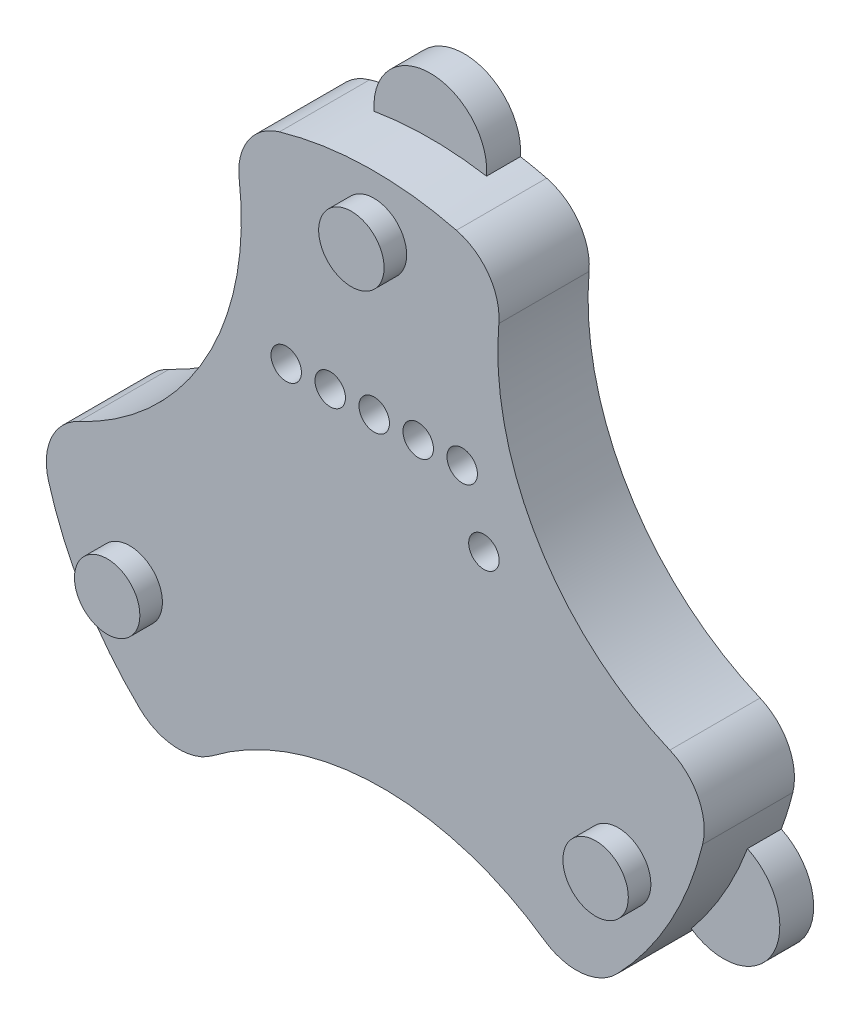
SolidWorks part; units mm, degrees
ref_plane "Спереди" through (0, 0, 0) normal (0, 0, 1) x (1, 0, 0)
ref_plane "Сверху" through (0, 0, 0) normal (0, 1, 0) x (1, 0, 0)
ref_plane "Справа" through (0, 0, 0) normal (1, 0, 0) x (0, 0, -1)
sketch "Sketch1" plane through (0, 0, 0) normal (0, 0, 1) x (1, 0, 0)
  line L0 (3.9, 6.755) -> (7.8, 0) construction
  line L2 (5.85, 10.1325) -> (11.7, 0) construction
  line L4 (7.8, 13.51) -> (15.6, 0) construction
  circle A61 centre (0, 0) radius 20
  circle A131 centre (0, 0) radius 1.25
  circle A484 centre (3.9, 0) radius 1.25
  circle A485 centre (7.8, 0) radius 1.25
  circle A486 centre (11.7, 0) radius 1.25
  circle A487 centre (15.6, 0) radius 1.25
  circle A488 centre (1.95, -3.3775) radius 1.25
  circle A489 centre (3.9, -6.755) radius 1.25
  circle A490 centre (5.85, -10.1325) radius 1.25
  circle A491 centre (7.8, -13.51) radius 1.25
  circle A492 centre (-1.95, -3.3775) radius 1.25
  circle A493 centre (-3.9, -6.755) radius 1.25
  circle A494 centre (-5.85, -10.1325) radius 1.25
  circle A495 centre (-7.8, -13.51) radius 1.25
  circle A496 centre (-3.9, 0) radius 1.25
  circle A497 centre (-7.8, 0) radius 1.25
  circle A498 centre (-11.7, 0) radius 1.25
  circle A499 centre (-15.6, 0) radius 1.25
  circle A500 centre (-1.95, 3.3775) radius 1.25
  circle A501 centre (-3.9, 6.755) radius 1.25
  circle A502 centre (-5.85, 10.1325) radius 1.25
  circle A503 centre (-7.8, 13.51) radius 1.25
  circle A504 centre (1.95, 3.3775) radius 1.25
  circle A505 centre (3.9, 6.755) radius 1.25
  circle A506 centre (5.85, 10.1325) radius 1.25
  circle A507 centre (7.8, 13.51) radius 1.25
  circle A508 centre (5.85, 3.3775) radius 1.25
  circle A509 centre (7.8, 6.755) radius 1.25
  circle A510 centre (9.75, 3.3775) radius 1.25
  circle A511 centre (11.7, 6.755) radius 1.25
  circle A512 centre (9.7491, 10.1341) radius 1.25
  circle A513 centre (13.6509, 3.3759) radius 1.25
  circle A514 centre (5.85, -3.3791) radius 1.25
  circle A515 centre (9.75, -3.3791) radius 1.25
  circle A516 centre (7.8, -6.7566) radius 1.25
  circle A517 centre (11.7, -6.7566) radius 1.25
  circle A518 centre (9.7491, -10.1356) radius 1.25
  circle A519 centre (13.6509, -3.3775) radius 1.25
  circle A520 centre (-0.0013, -6.7573) radius 1.25
  circle A521 centre (1.9487, -10.1348) radius 1.25
  circle A522 centre (-1.9513, -10.1348) radius 1.25
  circle A523 centre (-0.0013, -13.5123) radius 1.25
  circle A524 centre (-3.9032, -13.5123) radius 1.25
  circle A525 centre (3.9005, -13.5123) radius 1.25
  circle A526 centre (-5.8527, -3.3791) radius 1.25
  circle A527 centre (-7.8027, -6.7566) radius 1.25
  circle A528 centre (-9.7527, -3.3791) radius 1.25
  circle A529 centre (-11.7027, -6.7566) radius 1.25
  circle A530 centre (-13.6536, -3.3775) radius 1.25
  circle A531 centre (-9.7518, -10.1356) radius 1.25
  circle A532 centre (-5.8527, 3.3775) radius 1.25
  circle A533 centre (-9.7527, 3.3775) radius 1.25
  circle A534 centre (-7.8027, 6.755) radius 1.25
  circle A535 centre (-11.7027, 6.755) radius 1.25
  circle A536 centre (-9.7518, 10.1341) radius 1.25
  circle A537 centre (-13.6536, 3.3759) radius 1.25
  circle A538 centre (-0.0014, 6.7558) radius 1.25
  circle A539 centre (-1.9514, 10.1333) radius 1.25
  circle A540 centre (1.9486, 10.1333) radius 1.25
  circle A541 centre (-0.0014, 13.5108) radius 1.25
  circle A542 centre (3.9005, 13.5108) radius 1.25
  circle A543 centre (-3.9032, 13.5108) radius 1.25
  circle A544 centre (13.65, -1.1258) radius 2.2517 construction
  circle A545 centre (11.7009, -4.5044) radius 2.2522 construction
  circle A546 centre (9.75, -7.8834) radius 2.2522 construction
  circle A547 centre (7.7987, -11.2591) radius 2.2509 construction
  circle A548 centre (13.65, -1.1258) radius 0.65
  circle A549 centre (11.7009, -4.5044) radius 0.65
  circle A550 centre (9.75, -7.8834) radius 0.65
  circle A551 centre (7.7987, -11.2591) radius 0.65
  circle A552 centre (9.75, -1.1258) radius 0.65
  circle A553 centre (7.8009, -4.5044) radius 0.65
  circle A554 centre (5.85, -7.8834) radius 0.65
  circle A555 centre (3.8987, -11.2591) radius 0.65
  circle A556 centre (5.85, -1.1258) radius 0.65
  circle A557 centre (3.9009, -4.5044) radius 0.65
  circle A558 centre (1.95, -7.8834) radius 0.65
  circle A559 centre (-0.0013, -11.2591) radius 0.65
  circle A560 centre (1.95, -1.1258) radius 0.65
  circle A561 centre (0.0009, -4.5044) radius 0.65
  circle A562 centre (-1.95, -7.8834) radius 0.65
  circle A563 centre (-3.9013, -11.2591) radius 0.65
  circle A564 centre (-1.95, -1.1258) radius 0.65
  circle A565 centre (-3.8991, -4.5044) radius 0.65
  circle A566 centre (-5.85, -7.8834) radius 0.65
  circle A567 centre (-7.8013, -11.2591) radius 0.65
  circle A568 centre (-5.85, -1.1258) radius 0.65
  circle A569 centre (-7.7991, -4.5044) radius 0.65
  circle A570 centre (-9.75, -7.8834) radius 0.65
  circle A572 centre (-9.75, -1.1258) radius 0.65
  circle A573 centre (-11.6991, -4.5044) radius 0.65
  circle A576 centre (-13.65, -1.1258) radius 0.65
  circle A587 centre (0, 2.2517) radius 2.2517 construction
  circle A588 centre (0, 2.2517) radius 0.65
  circle A589 centre (3.9, 2.2517) radius 0.65
  circle A590 centre (7.8, 2.2517) radius 0.65
  circle A591 centre (11.7, 2.2517) radius 0.65
  circle A592 centre (15.6, 2.2517) radius 0.65
  circle A593 centre (1.9491, 5.6297) radius 2.2522 construction
  circle A594 centre (1.9491, 5.6297) radius 0.65
  circle A595 centre (5.8491, 5.6297) radius 0.65
  circle A596 centre (9.7491, 5.6297) radius 0.65
  circle A597 centre (13.6491, 5.6297) radius 0.65
  circle A598 centre (3.8991, 9.0072) radius 2.2522 construction
  circle A599 centre (3.8991, 9.0072) radius 0.65
  circle A600 centre (7.7991, 9.0072) radius 0.65
  circle A601 centre (11.6991, 9.0072) radius 0.65
  circle A602 centre (5.85, 12.3842) radius 2.2517 construction
  circle A603 centre (5.85, 12.3842) radius 0.65
  circle A604 centre (9.75, 12.3842) radius 0.65
  circle A605 centre (5.85, -14.6358) radius 0.65
  circle A606 centre (1.9509, -14.6353) radius 0.65
  circle A607 centre (-1.9491, -14.6353) radius 0.65
  circle A608 centre (-5.85, -14.6358) radius 0.65
  circle A609 centre (-15.6, 2.2517) radius 0.65
  circle A610 centre (-13.65, 5.6281) radius 0.65
  circle A611 centre (-11.7, 9.0056) radius 0.65
  circle A612 centre (-9.75, 12.3842) radius 0.65
  circle A613 centre (-5.85, 12.3842) radius 0.65
  circle A614 centre (-1.95, 12.3842) radius 0.65
  circle A615 centre (1.95, 12.3842) radius 0.65
  circle A616 centre (-7.8, 9.0056) radius 0.65
  circle A617 centre (-9.75, 5.6281) radius 0.65
  circle A618 centre (-11.7, 2.2517) radius 0.65
  circle A619 centre (-3.9, 9.0056) radius 0.65
  circle A620 centre (-5.85, 5.6281) radius 0.65
  circle A621 centre (-7.8, 2.2517) radius 0.65
  circle A622 centre (0, 9.0056) radius 0.65
  circle A623 centre (-1.95, 5.6281) radius 0.65
  circle A624 centre (-3.9, 2.2517) radius 0.65
  circle A625 centre (-15.5991, -4.5044) radius 0.65
  circle A626 centre (-13.65, -7.8834) radius 0.65
  circle A627 centre (-17.55, -7.8834) radius 0.65
  circle A628 centre (-19.5013, -11.2591) radius 0.65
  circle A629 centre (-15.6013, -11.2591) radius 0.65
  circle A630 centre (-11.7013, -11.2591) radius 0.65
  point P51 (0, 0)
  point P125 (-0.0013, -0.0008)
  point P231 (0, 0)
  dimension "D1" = 5
  dimension "D3" = 6
  dimension "D5" = 8
  dimension "D7" = 4
  dimension "D11" = 4
  dimension "D2" = 6
  dimension "D6" = 5
  dimension "D8" = 3
  dimension "D9" = 2
  dimension "D4" = 1.3
  dimension "D10" = 3
ref_plane "Plane1" through (0, 0, 10) normal (0, 0, 1) x (1, 0, 0)
sketch "Sketch2" plane through (0, 0, 10) normal (0, 0, 1) x (1, 0, 0)
  circle A52 centre (0, 0) radius 16.85 construction
  circle A53 centre (0, 0) radius 18.85
  circle A80 centre (7.8243, 11.3015) radius 1.3501
  circle A81 centre (5.85, 12.3842) radius 2.2517 construction
  circle A82 centre (3.9243, 11.3015) radius 1.3501
  circle A83 centre (0.0243, 11.3015) radius 1.3501
  circle A84 centre (-3.8757, 11.3015) radius 1.3501
  circle A85 centre (-7.7757, 11.3015) radius 1.3501
  circle A86 centre (9.7491, 5.6297) radius 1.3501
  circle A87 centre (0, 0) radius 11.2578 construction
  dimension "D15" = 2
  dimension "D2" = 5
extrude "Boss-Extrude1" add sketch "Sketch2" along normal blind 8
sketch "Sketch3" plane through (0, 0, 18) normal (0, 0, 1) x (1, 0, 0)
  circle A0 centre (0, 0) radius 17.6
  circle A1 centre (0, 0) radius 30
extrude "Boss-Extrude2" add sketch "Sketch3" against normal up to surface (8 mm away) up to face at (18.85, 0, 10)
sketch "Sketch4" plane through (0, 0, 18) normal (0, 0, 1) x (1, 0, 0)
  circle A0 centre (0, 0) radius 25 construction
  circle A1 centre (0, 25) radius 2.9
  circle A2 centre (21.6506, -12.5) radius 2.9
  circle A3 centre (-21.6506, -12.5) radius 2.9
  point P11 (0, 0)
  dimension "D1" = 3
extrude "Boss-Extrude3" add sketch "Sketch4" along normal blind 2
sketch "Sketch6" plane through (0, 0, 10) normal (0, 0, -1) x (-1, 0, 0)
  circle A0 centre (0, 30) radius 5
  circle A1 centre (0, 0) radius 30 construction
  circle A2 centre (25.9808, -15) radius 5
  circle A3 centre (-25.9808, -15) radius 5
  point P10 (0, 0)
  dimension "D1" = 3
extrude "Boss-Extrude4" add sketch "Sketch6" against normal blind 3
sketch "Sketch5" plane through (0, 0, 10) normal (0, 0, -1) x (-1, 0, 0)
  circle A0 centre (0, 25) radius 3
  circle A1 centre (21.6506, -12.5) radius 3
  circle A2 centre (-21.6506, -12.5) radius 3
extrude "Cut-Extrude1" cut sketch "Sketch5" against normal blind 3
sketch "Sketch7" plane through (0, 0, 10) normal (0, 0, -1) x (-1, 0, 0)
  line L0 (0, 0) -> (-35.9801, 21.6664) construction
  circle A0 centre (0, 0) radius 42 construction
  circle A1 centre (-35.9801, 21.6664) radius 25
  circle A2 centre (36.7537, 20.3265) radius 25
  circle A3 centre (-0.7736, -41.9929) radius 25
  point P11 (0, 0)
  dimension "D1" = 3
extrude "Cut-Extrude2" cut sketch "Sketch7" against normal blind 8
fillet "Fillet1" radius 5 6 edges at (-29.7735, -3.6793, 14) (-12.7099, 27.1746, 14) (18.0731, -23.945, 14) (-17.1789, -24.5944, 14) (11.7004, 27.6243, 14) (29.8888, -2.5802, 14)
sketch "Sketch8"
sketch_block_instance "Block1-1"
sketch_block "Block1" parameters "D1"=2, "D2"=3
sketch_block_instance "Block3-1"
sketch_block "Block3" parameters "D1"=2, "D2"=3
sketch "Sketch9" plane through (0, 0, 0) normal (0, 0, 1) x (1, 0, 0)
  line L0 (-7.8, 13.51) -> (-7.8027, 6.755) construction
  line L1 (-9.7518, 10.1341) -> (-5.85, 10.1325) construction
  line L2 (-7.8008, 11.6325) -> (-7.8019, 8.6325) construction
  line L3 (-6.8008, 11.6321) -> (-6.8019, 8.6321)
  line L4 (-8.8008, 11.6329) -> (-8.8019, 8.6329)
  line L5 (-4.9008, 11.6329) -> (-4.9019, 8.6329)
  line L6 (-2.9008, 11.6321) -> (-2.9019, 8.6321)
  line L7 (-3.9008, 11.6325) -> (-3.9019, 8.6325) construction
  line L8 (-1.0008, 11.6329) -> (-1.0019, 8.6329)
  line L9 (0.9992, 11.6321) -> (0.9981, 8.6321)
  line L10 (-0.0008, 11.6325) -> (-0.0019, 8.6325) construction
  line L11 (2.8992, 11.6329) -> (2.8981, 8.6329)
  line L12 (4.8992, 11.6321) -> (4.8981, 8.6321)
  line L13 (3.8992, 11.6325) -> (3.8981, 8.6325) construction
  line L14 (6.7992, 11.6329) -> (6.7981, 8.6329)
  line L15 (8.7992, 11.6321) -> (8.7981, 8.6321)
  line L16 (7.7992, 11.6325) -> (7.7981, 8.6325) construction
  line L17 (-9.7518, 10.1341) -> (-9.7527, 3.3775) construction
  line L18 (-11.7027, 6.755) -> (-7.8027, 6.755) construction
  line L19 (-10.7035, 1.877) -> (-10.702, 4.877)
  line L22 (-9.7527, 3.3775) -> (-5.8527, 3.3775) construction
  line L25 (-7.8027, 6.755) -> (-7.8, 0) construction
  line L26 (-7.8035, 1.8775) -> (-7.8019, 4.8775) construction
  line L27 (-8.8035, 1.878) -> (-8.8019, 4.878)
  line L28 (-6.8035, 1.877) -> (-6.8019, 4.877)
  line L29 (-2.9035, 1.877) -> (-2.9019, 4.877)
  line L30 (-4.9035, 1.878) -> (-4.9019, 4.878)
  line L31 (-3.9035, 1.8775) -> (-3.9019, 4.8775) construction
  line L32 (0.9965, 1.877) -> (0.9981, 4.877)
  line L33 (-1.0035, 1.878) -> (-1.0019, 4.878)
  line L34 (-0.0035, 1.8775) -> (-0.0019, 4.8775) construction
  line L35 (4.8965, 1.877) -> (4.8981, 4.877)
  line L36 (2.8965, 1.878) -> (2.8981, 4.878)
  line L37 (3.8965, 1.8775) -> (3.8981, 4.8775) construction
  line L38 (8.7965, 1.877) -> (8.7981, 4.877)
  line L39 (6.7965, 1.878) -> (6.7981, 4.878)
  line L40 (7.7965, 1.8775) -> (7.7981, 4.8775) construction
  line L41 (12.6965, 1.877) -> (12.6981, 4.877)
  line L42 (10.6965, 1.878) -> (10.6981, 4.878)
  line L43 (11.6965, 1.8775) -> (11.6981, 4.8775) construction
  line L44 (-12.7035, 1.878) -> (-12.7019, 4.878)
  line L45 (-11.7035, 1.8775) -> (-11.702, 4.8775) construction
  line L46 (-9.7527, -3.3791) -> (-5.8527, -3.3791) construction
  line L47 (-7.8, 0) -> (-7.8027, -6.7566) construction
  line L48 (-7.8046, -4.8791) -> (-7.8008, -1.8791) construction
  line L49 (-8.8046, -4.8778) -> (-8.8008, -1.8778)
  line L50 (-6.8046, -4.8804) -> (-6.8008, -1.8804)
  line L51 (-2.9046, -4.8804) -> (-2.9008, -1.8804)
  line L52 (-4.9046, -4.8778) -> (-4.9008, -1.8778)
  line L53 (-3.9046, -4.8791) -> (-3.9008, -1.8791) construction
  line L54 (0.9954, -4.8804) -> (0.9992, -1.8804)
  line L55 (-1.0046, -4.8778) -> (-1.0008, -1.8778)
  line L56 (-0.0046, -4.8791) -> (-0.0008, -1.8791) construction
  line L57 (4.8954, -4.8804) -> (4.8992, -1.8804)
  line L58 (2.8954, -4.8778) -> (2.8992, -1.8778)
  line L59 (3.8954, -4.8791) -> (3.8992, -1.8791) construction
  line L60 (8.7954, -4.8804) -> (8.7992, -1.8804)
  line L61 (6.7954, -4.8778) -> (6.7992, -1.8778)
  line L62 (7.7954, -4.8791) -> (7.7992, -1.8791) construction
  line L63 (12.6954, -4.8804) -> (12.6992, -1.8804)
  line L64 (10.6954, -4.8778) -> (10.6992, -1.8778)
  line L65 (11.6954, -4.8791) -> (11.6992, -1.8791) construction
  line L66 (-10.7046, -4.8804) -> (-10.7008, -1.8804)
  line L67 (-12.7046, -4.8778) -> (-12.7008, -1.8778)
  line L68 (-11.7046, -4.8791) -> (-11.7008, -1.8791) construction
  line L69 (-9.7518, -10.1356) -> (-5.482, -10.1356) construction
  line L70 (-7.8027, -6.7566) -> (-7.8, -13.51) construction
  line L71 (-7.8007, -8.6356) -> (-7.8007, -11.6356) construction
  line L72 (-6.8007, -8.6356) -> (-6.8007, -11.6356)
  line L73 (-8.8007, -8.6356) -> (-8.8007, -11.6356)
  line L74 (-4.9007, -8.6356) -> (-4.9007, -11.6356)
  line L75 (-2.9007, -8.6356) -> (-2.9007, -11.6356)
  line L76 (-3.9007, -8.6356) -> (-3.9007, -11.6356) construction
  line L77 (-1.0007, -8.6356) -> (-1.0007, -11.6356)
  line L78 (0.9993, -8.6356) -> (0.9993, -11.6356)
  line L79 (-0.0007, -8.6356) -> (-0.0007, -11.6356) construction
  line L80 (2.8993, -8.6356) -> (2.8993, -11.6356)
  line L81 (4.8993, -8.6356) -> (4.8993, -11.6356)
  line L82 (3.8993, -8.6356) -> (3.8993, -11.6356) construction
  line L83 (6.7993, -8.6356) -> (6.7993, -11.6356)
  line L84 (8.7993, -8.6356) -> (8.7993, -11.6356)
  line L85 (7.7993, -8.6356) -> (7.7993, -11.6356) construction
  arc A0 (-6.8008, 11.6321) -> (-8.8008, 11.6329) centre (-7.8008, 11.6325) ccw
  arc A1 (-8.8019, 8.6329) -> (-6.8019, 8.6321) centre (-7.8019, 8.6325) ccw
  arc A2 (-2.9008, 11.6321) -> (-4.9008, 11.6329) centre (-3.9008, 11.6325) ccw
  arc A3 (-4.9019, 8.6329) -> (-2.9019, 8.6321) centre (-3.9019, 8.6325) ccw
  arc A4 (0.9992, 11.6321) -> (-1.0008, 11.6329) centre (-0.0008, 11.6325) ccw
  arc A5 (-1.0019, 8.6329) -> (0.9981, 8.6321) centre (-0.0019, 8.6325) ccw
  arc A6 (4.8992, 11.6321) -> (2.8992, 11.6329) centre (3.8992, 11.6325) ccw
  arc A7 (2.8981, 8.6329) -> (4.8981, 8.6321) centre (3.8981, 8.6325) ccw
  arc A8 (8.7992, 11.6321) -> (6.7992, 11.6329) centre (7.7992, 11.6325) ccw
  arc A9 (6.7981, 8.6329) -> (8.7981, 8.6321) centre (7.7981, 8.6325) ccw
  arc A14 (-8.8035, 1.878) -> (-6.8035, 1.877) centre (-7.8035, 1.8775) ccw
  arc A15 (-6.8019, 4.877) -> (-8.8019, 4.878) centre (-7.8019, 4.8775) ccw
  arc A16 (-4.9035, 1.878) -> (-2.9035, 1.877) centre (-3.9035, 1.8775) ccw
  arc A17 (-2.9019, 4.877) -> (-4.9019, 4.878) centre (-3.9019, 4.8775) ccw
  arc A18 (-1.0035, 1.878) -> (0.9965, 1.877) centre (-0.0035, 1.8775) ccw
  arc A19 (0.9981, 4.877) -> (-1.0019, 4.878) centre (-0.0019, 4.8775) ccw
  arc A20 (2.8965, 1.878) -> (4.8965, 1.877) centre (3.8965, 1.8775) ccw
  arc A21 (4.8981, 4.877) -> (2.8981, 4.878) centre (3.8981, 4.8775) ccw
  arc A22 (6.7965, 1.878) -> (8.7965, 1.877) centre (7.7965, 1.8775) ccw
  arc A23 (8.7981, 4.877) -> (6.7981, 4.878) centre (7.7981, 4.8775) ccw
  arc A24 (10.6965, 1.878) -> (12.6965, 1.877) centre (11.6965, 1.8775) ccw
  arc A25 (12.6981, 4.877) -> (10.6981, 4.878) centre (11.6981, 4.8775) ccw
  arc A26 (-12.7035, 1.878) -> (-10.7035, 1.877) centre (-11.7035, 1.8775) ccw
  arc A27 (-10.702, 4.877) -> (-12.7019, 4.878) centre (-11.702, 4.8775) ccw
  arc A28 (-8.8046, -4.8778) -> (-6.8046, -4.8804) centre (-7.8046, -4.8791) ccw
  arc A29 (-6.8008, -1.8804) -> (-8.8008, -1.8778) centre (-7.8008, -1.8791) ccw
  arc A30 (-4.9046, -4.8778) -> (-2.9046, -4.8804) centre (-3.9046, -4.8791) ccw
  arc A31 (-2.9008, -1.8804) -> (-4.9008, -1.8778) centre (-3.9008, -1.8791) ccw
  arc A32 (-1.0046, -4.8778) -> (0.9954, -4.8804) centre (-0.0046, -4.8791) ccw
  arc A33 (0.9992, -1.8804) -> (-1.0008, -1.8778) centre (-0.0008, -1.8791) ccw
  arc A34 (2.8954, -4.8778) -> (4.8954, -4.8804) centre (3.8954, -4.8791) ccw
  arc A35 (4.8992, -1.8804) -> (2.8992, -1.8778) centre (3.8992, -1.8791) ccw
  arc A36 (6.7954, -4.8778) -> (8.7954, -4.8804) centre (7.7954, -4.8791) ccw
  arc A37 (8.7992, -1.8804) -> (6.7992, -1.8778) centre (7.7992, -1.8791) ccw
  arc A38 (10.6954, -4.8778) -> (12.6954, -4.8804) centre (11.6954, -4.8791) ccw
  arc A39 (12.6992, -1.8804) -> (10.6992, -1.8778) centre (11.6992, -1.8791) ccw
  arc A40 (-12.7046, -4.8778) -> (-10.7046, -4.8804) centre (-11.7046, -4.8791) ccw
  arc A41 (-10.7008, -1.8804) -> (-12.7008, -1.8778) centre (-11.7008, -1.8791) ccw
  arc A42 (-6.8007, -8.6356) -> (-8.8007, -8.6356) centre (-7.8007, -8.6356) ccw
  arc A43 (-8.8007, -11.6356) -> (-6.8007, -11.6356) centre (-7.8007, -11.6356) ccw
  arc A44 (-2.9007, -8.6356) -> (-4.9007, -8.6356) centre (-3.9007, -8.6356) ccw
  arc A45 (-4.9007, -11.6356) -> (-2.9007, -11.6356) centre (-3.9007, -11.6356) ccw
  arc A46 (0.9993, -8.6356) -> (-1.0007, -8.6356) centre (-0.0007, -8.6356) ccw
  arc A47 (-1.0007, -11.6356) -> (0.9993, -11.6356) centre (-0.0007, -11.6356) ccw
  arc A48 (4.8993, -8.6356) -> (2.8993, -8.6356) centre (3.8993, -8.6356) ccw
  arc A49 (2.8993, -11.6356) -> (4.8993, -11.6356) centre (3.8993, -11.6356) ccw
  arc A50 (8.7993, -8.6356) -> (6.7993, -8.6356) centre (7.7993, -8.6356) ccw
  arc A51 (6.7993, -11.6356) -> (8.7993, -11.6356) centre (7.7993, -11.6356) ccw
  circle A52 centre (0, 0) radius 16.85 construction
  circle A53 centre (0, 0) radius 18.85
  point P10 (-7.8014, 10.1325)
  point P18 (-3.9014, 10.1325)
  point P25 (-0.0014, 10.1325)
  point P32 (3.8986, 10.1325)
  point P39 (7.7986, 10.1325)
  point P50 (-11.7027, 3.3775)
  point P58 (-7.8027, 3.3775)
  point P68 (-3.9027, 3.3775)
  point P75 (-0.0027, 3.3775)
  point P82 (3.8973, 3.3775)
  point P89 (7.7973, 3.3775)
  point P96 (11.6973, 3.3775)
  point P108 (-7.8027, -3.3791)
  point P116 (-3.9027, -3.3791)
  point P123 (-0.0027, -3.3791)
  point P130 (3.8973, -3.3791)
  point P137 (7.7973, -3.3791)
  point P144 (11.6973, -3.3791)
  point P151 (-11.7027, -3.3791)
  point P162 (-7.8007, -10.1356)
  point P170 (-3.9007, -10.1356)
  point P177 (-0.0007, -10.1356)
  point P184 (3.8993, -10.1356)
  point P191 (7.7993, -10.1356)
  dimension "D1" = 2
  dimension "D15" = 2
  dimension "D2" = 3
  dimension "D4" = 2
  dimension "D5" = 3
  dimension "D6" = 2
  dimension "D7" = 3
  dimension "D9" = 2
  dimension "D12" = 3
  dimension "D13" = 2
  dimension "D3" = 5
  dimension "D8" = 6
  dimension "D10" = 6
  dimension "D11" = 2
  dimension "D14" = 5
